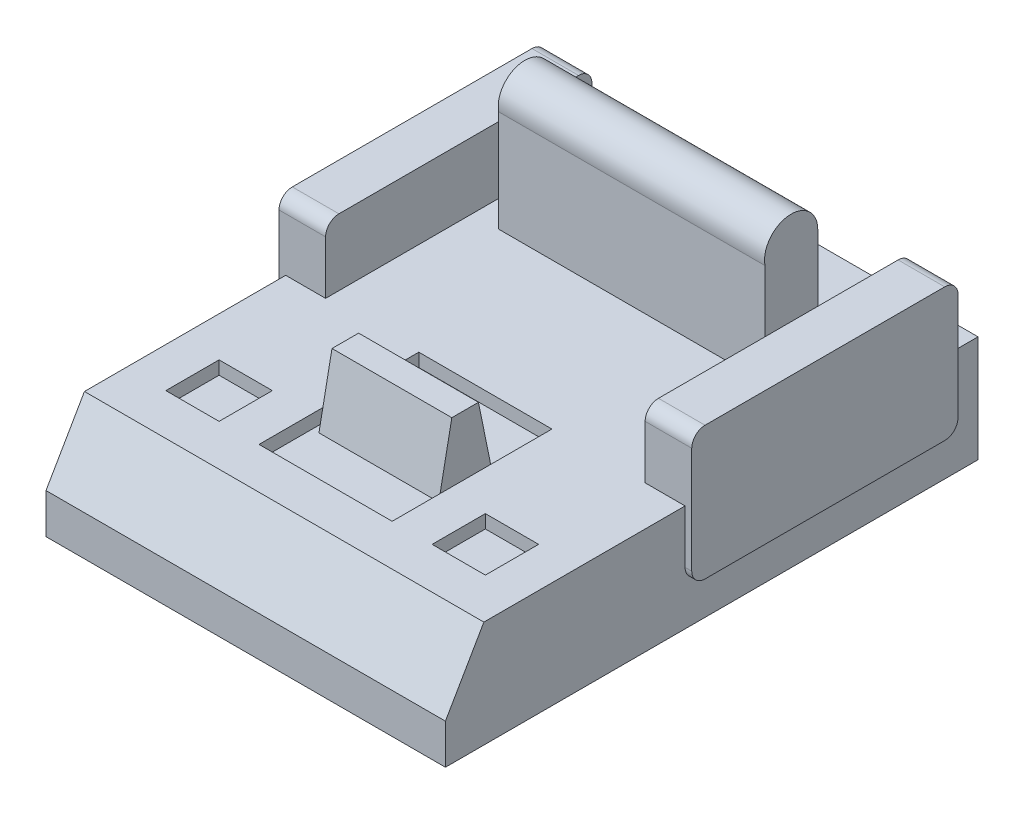
SolidWorks part; units mm, degrees
ref_plane "前视基准面" through (0, 0, 0) normal (0, 0, 1) x (1, 0, 0)
ref_plane "上视基准面" through (0, 0, 0) normal (0, 1, 0) x (1, 0, 0)
ref_plane "右视基准面" through (0, 0, 0) normal (1, 0, 0) x (0, 0, -1)
other "Configuration Table"
sketch "草图1" plane through (0, 0, 0) normal (0, 1, 0) x (1, 0, 0)
  line L1 (-15, -20) -> (15, -20)
  line L2 (-15, -20) -> (-15, 20)
  line L3 (-15, 20) -> (15, 20)
  line L4 (15, -20) -> (15, 20)
  line L5 (-15, -20) -> (15, 20) construction
  line L6 (-15, 20) -> (15, -20) construction
  point P0 (0, 0)
  dimension "D1" = 40
  dimension "D2" = 30
extrude "凸台-拉伸1" add sketch "草图1" along normal blind 8
chamfer "倒角1" distance 5 angle 30 1 edges at (0, 8, 20)
ref_plane "基准面1" through (0, 12, 0) normal (0, 1, 0) x (1, 0, 0)
sketch "草图4" plane through (0, 8, 0) normal (0, 1, 0) x (1, 0, 0)
  line L2 (-12, -14) -> (-8, -14)
  line L3 (-8, -14) -> (-8, -10)
  line L4 (-8, -10) -> (-12, -10)
  line L5 (-12, -10) -> (-12, -14)
  line L6 (0, 20) -> (0, -22.0611) construction
  line L7 (15, 20) -> (-15, 20) construction
  line L8 (12, -10) -> (12, -14)
  line L9 (8, -10) -> (12, -10)
  line L10 (8, -14) -> (8, -10)
  line L11 (12, -14) -> (8, -14)
  point P0 (0, 0)
  dimension "D1" = 24
  dimension "D2" = 4
sketch "草图6" plane through (15, 0, 0) normal (1, 0, 0) x (0, 0, -1)
  line L0 (20, 5.5751) -> (18, 5.5751) construction
  line L7 (20, 8) -> (20, 0) construction
  line L8 (18, 12) -> (18, 4)
  line L9 (17, 13) -> (-1, 13)
  line L10 (-2, 12) -> (-2, 4)
  line L13 (-1, 3) -> (17, 3)
  line L14 (-20, 0) -> (20, 0) construction
  arc A0 (-1, 3) -> (-2, 4) centre (-1, 4) cw
  arc A1 (17, 3) -> (18, 4) centre (17, 4) ccw
  arc A2 (18, 12) -> (17, 13) centre (17, 12) ccw
  arc A3 (-1, 13) -> (-2, 12) centre (-1, 12) ccw
  point P12 (-2, 3)
  point P17 (18, 13)
  point P20 (-2, 13)
  dimension "D5" = 1
  dimension "D1" = 2
  dimension "D2" = 3
  dimension "D3" = 20
  dimension "D4" = 10
extrude "凸台-拉伸2" add sketch "草图6" along normal blind 0.5 and the other way blind 3
mirror "镜向2" about plane through (0, 0, 0) normal (1, 0, 0) of "凸台-拉伸2"
sketch "草图10" plane through (0, 0, 0) normal (1, 0, 0) x (0, 0, -1)
  line L4 (9, 8) -> (9, 15.631)
  line L6 (12.9657, 16) -> (12.9657, 8)
  line L7 (9, 8) -> (12.9657, 8)
  arc A0 (12.9657, 16) -> (9, 15.631) centre (10.9657, 16) ccw
  dimension "D2" = 2
  dimension "D1" = 29
extrude "凸台-拉伸3" add sketch "草图10" along normal blind 10 and the other way blind 10
extrude "切除-拉伸2" cut sketch "草图4" against normal blind 1
sketch "草图12" plane through (0, 8, 0) normal (0, 1, 0) x (1, 0, 0)
  line L0 (-12, -14) -> (-8, -14) construction
  line L1 (-5, -14) -> (5, -14)
  line L2 (-5, -14) -> (-5, -2)
  line L3 (-5, -2) -> (5, -2)
  line L4 (5, -14) -> (5, -2)
  line L5 (-5, -14) -> (5, -2) construction
  line L6 (-5, -2) -> (5, -14) construction
  point P0 (0, -8)
  point P7 (0, 0)
  point P8 (0, -8)
  dimension "D1" = 10
  dimension "D2" = 12
extrude "切除-拉伸3" cut sketch "草图12" against normal blind 1
sketch "草图13" plane through (0, 7, 0) normal (0, 1, 0) x (1, 0, 0)
  line L0 (-5, -8) -> (5, -8) construction
  line L3 (-5, -2) -> (-5, -14) construction
  line L4 (5, -14) -> (5, -2) construction
  line L6 (-4.5, -10) -> (4.5, -10)
  line L7 (-4.5, -10) -> (-4.5, -6)
  line L8 (-4.5, -6) -> (4.5, -6)
  line L9 (4.5, -10) -> (4.5, -6)
  line L10 (-4.5, -10) -> (4.5, -6) construction
  line L11 (-4.5, -6) -> (4.5, -10) construction
  point P3 (0, -2)
  point P7 (0, -8)
  point P12 (5, -8)
  dimension "D1" = 4
  dimension "D2" = 9
sketch "草图14" plane through (0, 12, 0) normal (0, 1, 0) x (1, 0, 0)
  line L5 (-4.5, -7.02) -> (4.5, -7.02)
  line L9 (4.5, -7.02) -> (4.5, -9.02)
  line L11 (4.5, -9.02) -> (-4.5, -9.02)
  line L13 (-4.5, -9.02) -> (-4.5, -7.02)
  line L16 (5, -8) -> (-7.4681, -8) construction
  dimension "D1" = 2
  dimension "D2" = 9
loft "放样3" add profiles "草图14", "草图13"
